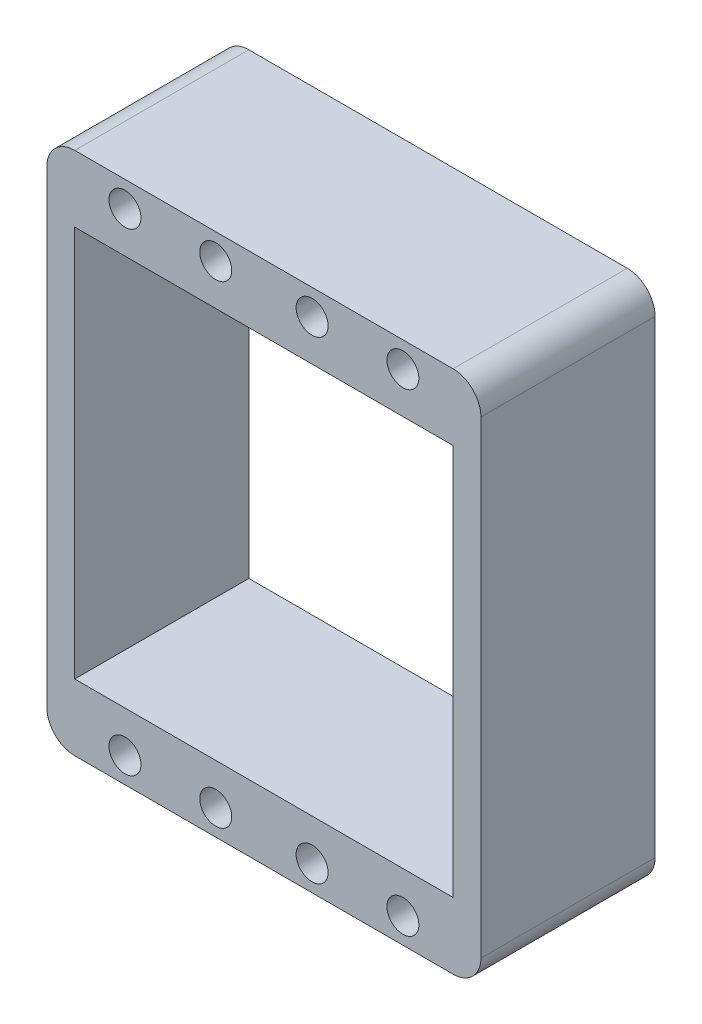
SolidWorks part; units mm, degrees
material "ABS"
ref_plane "Front Plane" through (0, 0, 0) normal (0, 0, 1) x (1, 0, 0)
ref_plane "Top Plane" through (0, 0, 0) normal (0, 1, 0) x (1, 0, 0)
ref_plane "Right Plane" through (0, 0, 0) normal (1, 0, 0) x (0, 0, -1)
sketch "Sketch1" plane through (0, 0, 0) normal (0, 0, 1) x (1, 0, 0)
  line L0 (-23.425, 28.3) -> (23.425, 28.3)
  line L1 (-20.425, -21.125) -> (20.425, -21.125)
  line L2 (-20.425, -21.125) -> (-20.425, 21.125)
  line L3 (-20.425, 21.125) -> (20.425, 21.125)
  line L4 (20.425, -21.125) -> (20.425, 21.125)
  line L5 (-20.425, -21.125) -> (20.425, 21.125) construction
  line L6 (-20.425, 21.125) -> (20.425, -21.125) construction
  line L7 (23.425, 28.3) -> (23.425, -28.3)
  line L8 (23.425, -28.3) -> (-23.425, -28.3)
  line L9 (-23.425, -28.3) -> (-23.425, 28.3)
  line L10 (-23.425, 0) -> (23.425, 0) construction
  line L11 (0, -28.3) -> (0, 28.3) construction
  line L12 (-15, -25.55) -> (-5.2, -25.55) construction
  line L13 (5.2, -25.55) -> (15, -25.55) construction
  line L14 (-10.1, -21.125) -> (-10.1, -28.3) construction
  line L15 (10.1, -21.125) -> (10.1, -28.3) construction
  circle A0 centre (-15, -25.55) radius 1.725
  circle A1 centre (-5.2, -25.55) radius 1.725
  circle A2 centre (5.2, -25.55) radius 1.725
  circle A3 centre (15, -25.55) radius 1.725
  circle A4 centre (15, 25.55) radius 1.725
  circle A5 centre (5.2, 25.55) radius 1.725
  circle A6 centre (-5.2, 25.55) radius 1.725
  circle A7 centre (-15, 25.55) radius 1.725
  point P0 (0, 0)
  dimension "D8" = 3.45
  dimension "D1" = 51.1
  dimension "D2" = 3
  dimension "D3" = 40.85
  dimension "D4" = 42.25
  dimension "D5" = 9.8
  dimension "D6" = 30
  dimension "D7" = 2.75
extrude "Boss-Extrude1" add sketch "Sketch1" along normal blind 18.8
fillet "Fillet1" radius 3 4 edges at (-23.425, -28.3, 9.4) (23.425, -28.3, 9.4) (23.425, 28.3, 9.4) (-23.425, 28.3, 9.4)
equation "\"D8@Sketch1\"=3.00mm+\"print_free@Parameters@Parameters.SLDPRT\""
equation "\"D3@Sketch1\"=40.40mm+\"print_free@Parameters@Parameters.SLDPRT\""
equation "\"D4@Sketch1\"=41.8 + \"print_free@Parameters@Parameters.SLDPRT\""
